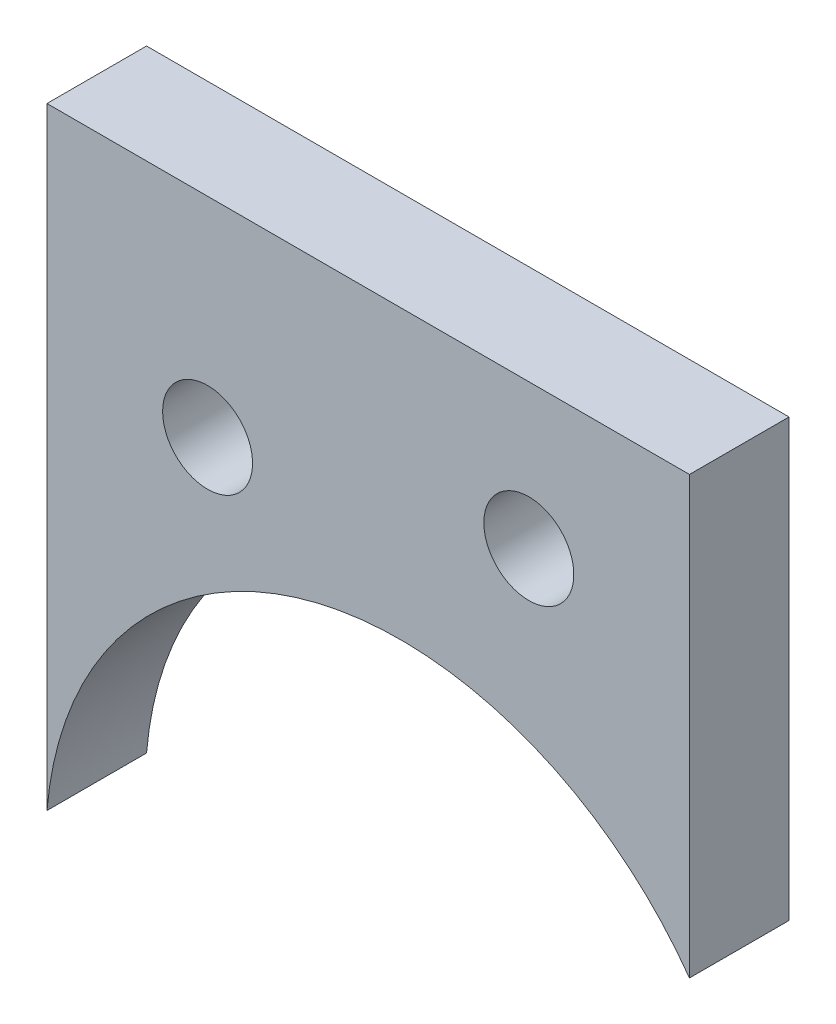
SolidWorks part; units mm, degrees
ref_plane "Front Plane" through (0, 0, 0) normal (0, 0, 1) x (1, 0, 0)
ref_plane "Top Plane" through (0, 0, 0) normal (0, 1, 0) x (1, 0, 0)
ref_plane "Right Plane" through (0, 0, 0) normal (1, 0, 0) x (0, 0, -1)
sketch "Sketch1" plane through (0, 0, 0) normal (0, 0, 1) x (1, 0, 0)
  line L2 (0, 0.9394) -> (0, 20)
  line L3 (0, 20) -> (20, 20)
  line L4 (20, 6.4251) -> (20, 20)
  circle A0 centre (5, 13.5) radius 1.4
  circle A1 centre (15, 15.5) radius 1.4
  arc A2 (20, 6.4251) -> (0, 0.9394) centre (11.01, 0) ccw
  point P11 (0, 0)
extrude "Boss-Extrude1" add sketch "Sketch1" along normal blind 3.1
